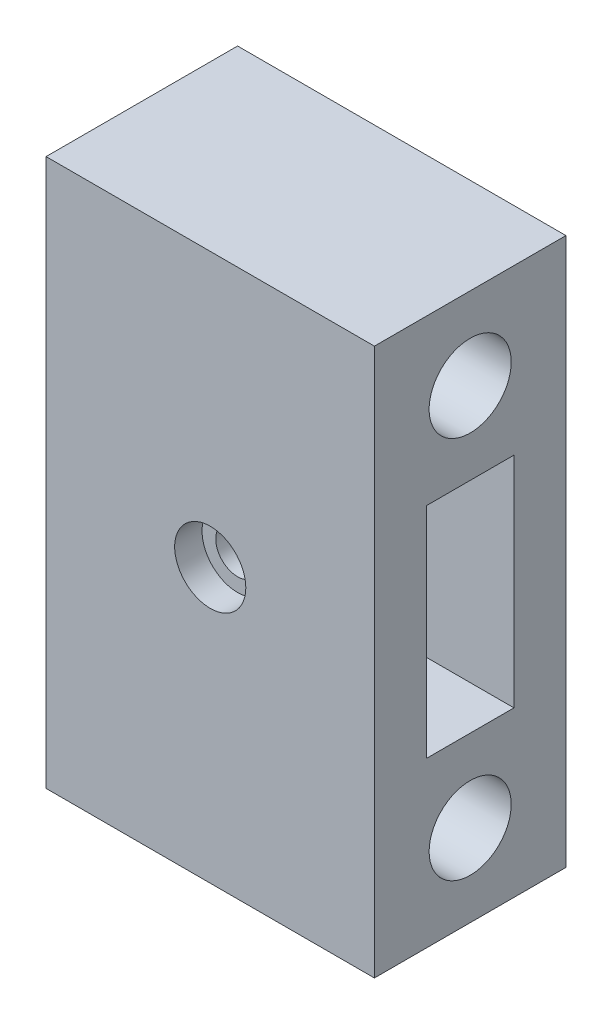
SolidWorks part; units mm, degrees
ref_plane "Front Plane" through (0, 0, 0) normal (0, 0, 1) x (1, 0, 0)
ref_plane "Top Plane" through (0, 0, 0) normal (0, 1, 0) x (1, 0, 0)
ref_plane "Right Plane" through (0, 0, 0) normal (1, 0, 0) x (0, 0, -1)
sketch "Sketch1" plane through (0, 0, 0) normal (0, 0, 1) x (1, 0, 0)
  line L1 (-30, -50) -> (30, -50)
  line L2 (-30, -50) -> (-30, 50)
  line L3 (-30, 50) -> (30, 50)
  line L4 (30, -50) -> (30, 50)
  line L5 (-30, -50) -> (30, 50) construction
  line L6 (-30, 50) -> (30, -50) construction
  point P0 (0, 0)
extrude "Boss-Extrude1" add sketch "Sketch1" along normal blind 35
sketch "Sketch3" plane through (30, 0, 0) normal (1, 0, 0) x (0, 0, -1)
  line L5 (-25.5, -20) -> (-9.5, -20)
  line L6 (-25.5, -20) -> (-25.5, 20)
  line L7 (-25.5, 20) -> (-9.5, 20)
  line L8 (-9.5, -20) -> (-9.5, 20)
  line L9 (-25.5, -20) -> (-9.5, 20) construction
  line L10 (-25.5, 20) -> (-9.5, -20) construction
  circle A1 centre (-17.5, 35) radius 7.5
  circle A2 centre (-17.5, -35) radius 7.5
  point P12 (-17.5, 0)
extrude "Cut-Extrude1" cut sketch "Sketch3" against normal blind 55
sketch "Sketch5" plane through (0, 0, 0) normal (0, 0, -1) x (-1, 0, 0)
  circle A0 centre (0, 0) radius 4
extrude "Cut-Extrude2" cut sketch "Sketch5" against normal through all both and the other way through all
sketch "Sketch7" plane through (0, 0, 35) normal (0, 0, 1) x (1, 0, 0)
  circle A0 centre (0, 0) radius 6.5
extrude "Cut-Extrude3" cut sketch "Sketch7" against normal blind 5
sketch "Sketch8" plane through (0, 0, 0) normal (0, 0, -1) x (-1, 0, 0)
  line L1 (0, 8.6666) -> (-7.5055, 4.3333)
  line L2 (-7.5055, 4.3333) -> (-7.5055, -4.3333)
  line L3 (-7.5055, -4.3333) -> (0, -8.6666)
  line L4 (0, -8.6666) -> (7.5055, -4.3333)
  line L5 (7.5055, -4.3333) -> (7.5055, 4.3333)
  line L6 (7.5055, 4.3333) -> (0, 8.6666)
  circle A0 centre (0, 0) radius 7.5055 construction
extrude "Cut-Extrude5" cut sketch "Sketch8" against normal blind 7.5 contours L6 L1 L2 L3 L4 L5
